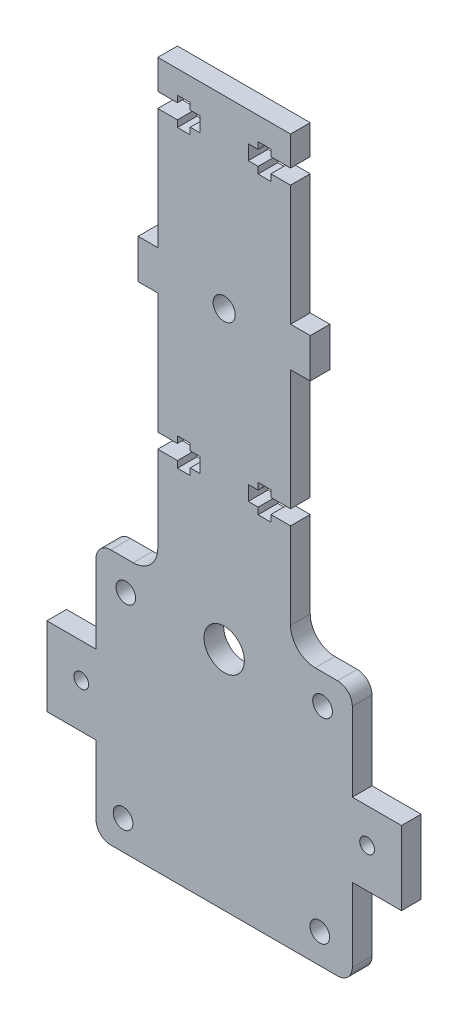
SolidWorks part; units mm, degrees
ref_plane "前视基准面" through (0, 0, 0) normal (0, 0, 1) x (1, 0, 0)
ref_plane "上视基准面" through (0, 0, 0) normal (0, 1, 0) x (1, 0, 0)
ref_plane "右视基准面" through (0, 0, 0) normal (1, 0, 0) x (0, 0, -1)
sketch "草图1" plane through (0, 0, 0) normal (0, 0, 1) x (1, 0, 0)
  line L1 (0, -10.137) -> (-4, -10.137)
  line L2 (-4, -10.137) -> (-4, -2.137)
  line L3 (-4, -2.137) -> (0, -2.137)
  line L4 (0, -2.137) -> (0, 22.363)
  line L5 (0, 22.363) -> (4, 22.363)
  line L6 (4, 22.363) -> (4, 21.013)
  line L7 (4, 21.013) -> (6.6, 21.013)
  line L8 (6.6, 21.013) -> (6.6, 22.363)
  line L9 (6.6, 22.363) -> (8.6, 22.363)
  line L10 (8.6, 22.363) -> (8.6, 25.363)
  line L11 (8.6, 25.363) -> (6.6, 25.363)
  line L12 (6.6, 25.363) -> (6.6, 26.713)
  line L13 (6.6, 26.713) -> (4, 26.713)
  line L14 (4, 26.713) -> (4, 25.363)
  line L15 (4, 25.363) -> (0, 25.363)
  line L16 (0, 25.363) -> (0, 31.363)
  line L17 (0, 31.363) -> (27, 31.363)
  line L18 (0, 25.363) -> (0, 22.363) construction
  line L20 (13.5, 31.363) -> (13.5, 28.363) construction
  line L21 (27, 25.363) -> (27, 22.363) construction
  line L22 (27, 25.363) -> (27, 31.363)
  line L23 (23, 25.363) -> (27, 25.363)
  line L24 (23, 26.713) -> (23, 25.363)
  line L25 (20.4, 26.713) -> (23, 26.713)
  line L26 (20.4, 25.363) -> (20.4, 26.713)
  line L27 (18.4, 25.363) -> (20.4, 25.363)
  line L28 (18.4, 22.363) -> (18.4, 25.363)
  line L29 (20.4, 22.363) -> (18.4, 22.363)
  line L30 (20.4, 21.013) -> (20.4, 22.363)
  line L31 (23, 21.013) -> (20.4, 21.013)
  line L32 (23, 22.363) -> (23, 21.013)
  line L33 (27, 22.363) -> (23, 22.363)
  line L34 (27, -2.137) -> (27, 22.363)
  line L35 (31, -2.137) -> (27, -2.137)
  line L36 (31, -10.137) -> (31, -2.137)
  line L37 (27, -10.137) -> (31, -10.137)
  line L39 (-4, -6.137) -> (31, -6.137) construction
  line L40 (13.5, -6.137) -> (13.5, -66.137) construction
  line L46 (-5, -60.137) -> (-9.56, -60.137)
  line L47 (-12.56, -63.137) -> (-12.56, -109.1331) construction
  line L48 (32, -60.137) -> (36.56, -60.137)
  line L49 (39.56, -63.137) -> (39.56, -109.1331) construction
  line L50 (36.56, -112.1331) -> (-9.56, -112.1331)
  line L51 (0, -37.637) -> (0, -34.637) construction
  line L52 (4, -37.637) -> (0, -37.637)
  line L53 (4, -38.987) -> (4, -37.637)
  line L54 (6.6, -38.987) -> (4, -38.987)
  line L55 (6.6, -37.637) -> (6.6, -38.987)
  line L56 (8.6, -37.637) -> (6.6, -37.637)
  line L57 (8.6, -34.637) -> (8.6, -37.637)
  line L58 (6.6, -34.637) -> (8.6, -34.637)
  line L59 (6.6, -33.287) -> (6.6, -34.637)
  line L60 (4, -33.287) -> (6.6, -33.287)
  line L61 (4, -34.637) -> (4, -33.287)
  line L62 (0, -34.637) -> (4, -34.637)
  line L63 (0, -34.637) -> (0, -10.137)
  line L64 (0, -37.637) -> (0, -55.137)
  line L65 (27, -37.637) -> (27, -34.637) construction
  line L66 (27, -37.637) -> (27, -55.137)
  line L67 (27, -34.637) -> (27, -10.137)
  line L68 (27, -34.637) -> (23, -34.637)
  line L69 (23, -34.637) -> (23, -33.287)
  line L70 (23, -33.287) -> (20.4, -33.287)
  line L71 (20.4, -33.287) -> (20.4, -34.637)
  line L72 (20.4, -34.637) -> (18.4, -34.637)
  line L73 (18.4, -34.637) -> (18.4, -37.637)
  line L74 (18.4, -37.637) -> (20.4, -37.637)
  line L75 (20.4, -37.637) -> (20.4, -38.987)
  line L76 (20.4, -38.987) -> (23, -38.987)
  line L77 (23, -38.987) -> (23, -37.637)
  line L78 (23, -37.637) -> (27, -37.637)
  line L79 (-12.56, -79.137) -> (-12.56, -63.137)
  line L80 (-12.56, -95.137) -> (-12.56, -109.1331)
  line L81 (39.56, -79.137) -> (39.56, -63.137)
  line L82 (39.56, -94.135) -> (39.56, -109.1331)
  line L83 (-12.56, -86.135) -> (-15.56, -86.135) construction
  line L84 (39.56, -86.135) -> (42.56, -86.135) construction
  line L85 (39.56, -79.137) -> (49.56, -79.137)
  line L86 (49.56, -79.137) -> (49.56, -94.135)
  line L87 (49.56, -94.135) -> (39.56, -94.135)
  line L88 (-12.56, -79.137) -> (-22.56, -79.137)
  line L89 (-22.56, -79.137) -> (-22.56, -95.137)
  line L90 (-22.56, -95.137) -> (-12.56, -95.137)
  circle A0 centre (13.5, -6.137) radius 2.25
  circle A1 centre (-6.5, -66.137) radius 2
  circle A2 centre (-7.058, -106.1331) radius 2
  circle A3 centre (32.942, -106.1331) radius 2
  circle A4 centre (33.5, -66.137) radius 2
  circle A5 centre (13.5, -66.137) radius 4.1
  arc A6 (32, -60.137) -> (27, -55.137) centre (32, -55.137) cw
  arc A7 (0, -55.137) -> (-5, -60.137) centre (-5, -55.137) cw
  arc A8 (39.56, -63.137) -> (36.56, -60.137) centre (36.56, -63.137) ccw
  arc A9 (39.56, -109.1331) -> (36.56, -112.1331) centre (36.56, -109.1331) cw
  arc A10 (-9.56, -112.1331) -> (-12.56, -109.1331) centre (-9.56, -109.1331) cw
  arc A11 (-9.56, -60.137) -> (-12.56, -63.137) centre (-9.56, -63.137) ccw
  circle A14 centre (-15.56, -86.135) radius 1.5
  circle A15 centre (42.56, -86.135) radius 1.5
  point P37 (13.5, -25.6947)
  point P84 (27, -60.137)
  point P87 (0, -60.137)
  dimension "D11" = 40
  dimension "D18" = 5
  dimension "D19" = 3
  dimension "D20" = 6.06
  dimension "D1" = 13.5
  dimension "D2" = 3
  dimension "D3" = 8
  dimension "D4" = 4
  dimension "D5" = 24.5
  dimension "D6" = 4
  dimension "D7" = 2
  dimension "D8" = 2.6
  dimension "D9" = 1.35
  dimension "D10" = 6
  dimension "D12" = 40
  dimension "D13" = 40
  dimension "D14" = 20
  dimension "D15" = 60
  dimension "D16" = 50
  dimension "D17" = 6
  dimension "D21" = 6.06
  dimension "D22" = 16
extrude "凸台-拉伸1" add sketch "草图1" along normal blind 4
sketch "草图2" plane through (27, 0, 0) normal (1, 0, 0) x (0, 0, -1)
  line L0 (-2, 25.363) -> (-2, 22.363)
  line L1 (-4, 25.363) -> (0, 25.363) construction
  line L2 (-4, 22.363) -> (0, 22.363) construction
  circle A0 centre (-2, 23.863) radius 1.5
